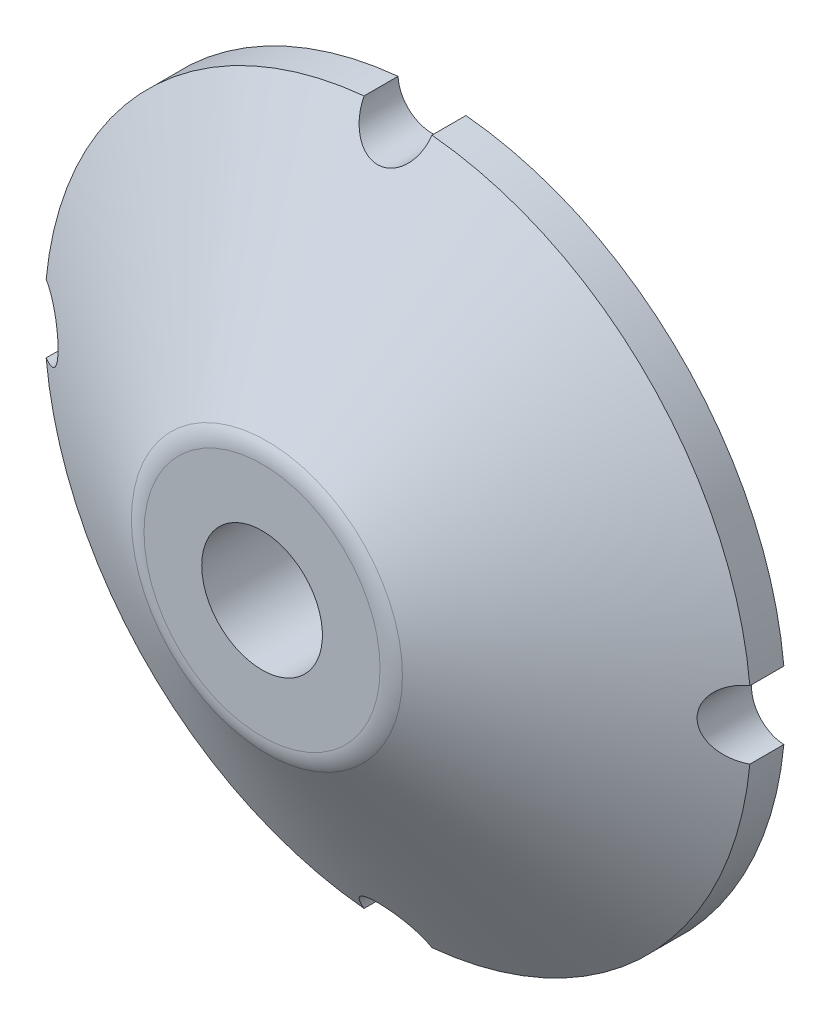
SolidWorks part; units mm, degrees
ref_plane "Front Plane" through (0, 0, 0) normal (0, 0, 1) x (1, 0, 0)
ref_plane "Top Plane" through (0, 0, 0) normal (0, 1, 0) x (1, 0, 0)
ref_plane "Right Plane" through (0, 0, 0) normal (1, 0, 0) x (0, 0, -1)
sketch "Sketch2" plane through (0, 0, 0) normal (1, 0, 0) x (0, 0, -1)
  line L0 (0, 0) -> (-10, 0) construction
  line L1 (0, 17) -> (0, 20.8)
  line L2 (0, 20.8) -> (-2, 20.8)
  line L3 (-2, 20.8) -> (-10, 7.5)
  line L4 (-7.6, 7.5) -> (-7.6, 5.3)
  line L5 (-7.6, 5.3) -> (0, 5.3)
  line L6 (0, 5.3) -> (0, 3.55)
  line L7 (0, 3.55) -> (-10, 3.55)
  line L8 (-10, 3.55) -> (-10, 7.5)
  line L14 (-7.6, 7.5) -> (-2, 17)
  line L15 (-2, 17) -> (0, 17)
  dimension "D1" = 41.6
  dimension "D2" = 10
  dimension "D3" = 10.6
  dimension "D4" = 7.1
  dimension "D5" = 15
  dimension "D6" = 7.6
  dimension "D10" = 15
  dimension "D12" = 3.8
  dimension "D13" = 2
  dimension "D15" = 2
revolve "Revolve1" add sketch "Sketch2" angle 360 about L0
sketch "Sketch3" plane through (0, 0, 0) normal (0, 0, 1) x (1, 0, 0)
  circle A0 centre (0, 20.8) radius 2
  circle A1 centre (0, 0) radius 20.8 construction
  circle A2 centre (20.8, 0) radius 2
  circle A3 centre (0, -20.8) radius 2
  circle A4 centre (-20.8, 0) radius 2
  dimension "D1" = 4
  dimension "D2" = 4
extrude "Cut-Extrude1" cut sketch "Sketch3" along normal up to next
fillet "Fillet1" radius 2 1 edges at (-7.5, 0, 10)
